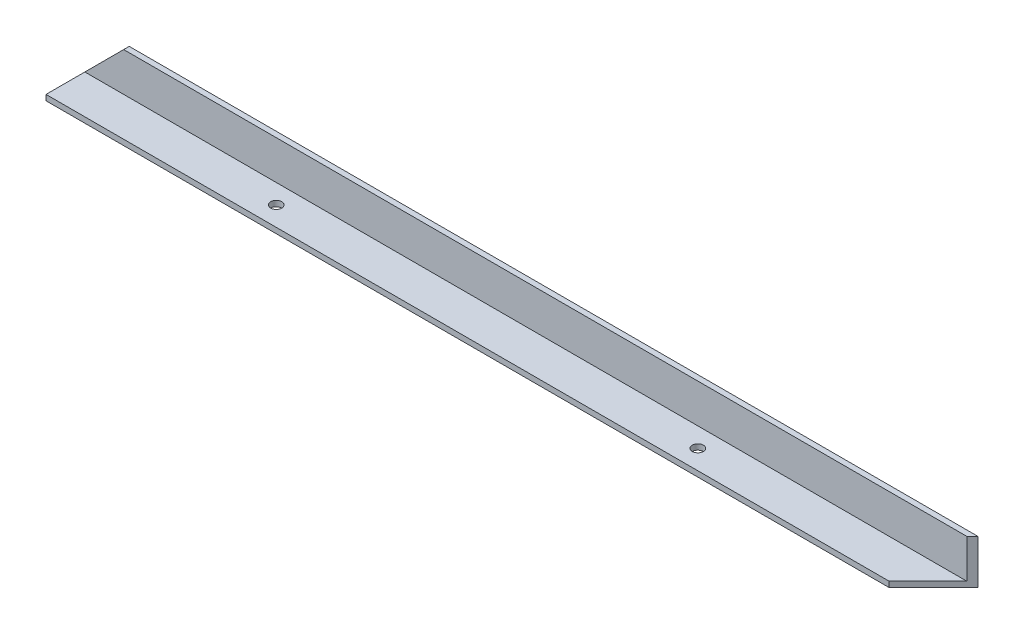
SolidWorks part; units mm, degrees
ref_plane "Front Plane" through (0, 0, 0) normal (0, 0, 1) x (1, 0, 0)
ref_plane "Top Plane" through (0, 0, 0) normal (0, 1, 0) x (1, 0, 0)
ref_plane "Right Plane" through (0, 0, 0) normal (1, 0, 0) x (0, 0, -1)
sketch "Sketch1" plane through (0, 0, 0) normal (0, 1, 0) x (1, 0, 0)
  line L1 (0, 0) -> (-508, 0)
  line L2 (0, 0) -> (0, -25.4)
  line L3 (0, -25.4) -> (-508, -25.4)
  line L4 (-508, 0) -> (-508, -25.4)
  dimension "D1" = 508
  dimension "D2" = 25.4
extrude "Boss-Extrude1" add sketch "Sketch1" along normal blind 3.175
sketch "Sketch2" plane through (0, 3.175, 0) normal (0, 1, 0) x (1, 0, 0)
  line L0 (0, -25.4) -> (0, 0) construction
  line L1 (-508, 0) -> (0, 0)
  line L2 (-508, 0) -> (-508, -3.175)
  line L3 (-508, -3.175) -> (0, -3.175)
  line L4 (0, 0) -> (0, -3.175)
  dimension "D1" = 3.175
extrude "Boss-Extrude2" add sketch "Sketch2" along normal blind 22.225
sketch "Sketch3" plane through (0, 25.4, 0) normal (0, 1, 0) x (1, 0, 0)
  line L0 (0, 0) -> (-52.3316, -52.3316)
  line L1 (-52.3316, -52.3316) -> (49.5361, -29.784)
  line L2 (49.5361, -29.784) -> (0, 0)
  line L3 (0, 0) -> (0.418, 0.0151)
  line L4 (-508, -3.175) -> (0, -3.175) construction
  point P7 (0, 0)
  dimension "D1" = 45
sketch "Sketch5" plane through (0, 0, 3.175) normal (0, 0, 1) x (1, 0, 0)
  line L0 (-508, 3.175) -> (-465.6734, 45.5016)
  line L1 (-465.6734, 45.5016) -> (-525.4558, 41.886)
  line L2 (-525.4558, 41.886) -> (-508, 3.175)
  line L3 (-508, 3.175) -> (0, 3.175) construction
  dimension "D1" = 45
extrude "Cut-Extrude2" cut sketch "Sketch5" against normal up to surface (3.175 mm away) up to face at (-254, 12.7, 0)
extrude "Cut-Extrude4" cut sketch "Sketch3" against normal up to surface (25.4 mm away) contours L0 L1 L2 up to face at (-254, 0, 12.7)
sketch "Sketch6" plane through (0, 3.175, 0) normal (0, 1, 0) x (1, 0, 0)
  line L0 (-266.7, -25.4) -> (-266.7, -3.175) construction
  line L1 (-508, -25.4) -> (-25.4, -25.4) construction
  line L2 (-485.775, -3.175) -> (-3.175, -3.175) construction
  circle A0 centre (-146.05, -14.2875) radius 3.175
  circle A1 centre (-387.35, -14.2875) radius 3.175
  dimension "D1" = 6.35
  dimension "D2" = 22.225
  dimension "D3" = 11.1125
  dimension "D4" = 241.3
  dimension "D5" = 120.65
extrude "Cut-Extrude5" cut sketch "Sketch6" against normal up to surface (3.175 mm away) up to face at (-260.35, 0, 12.7)
